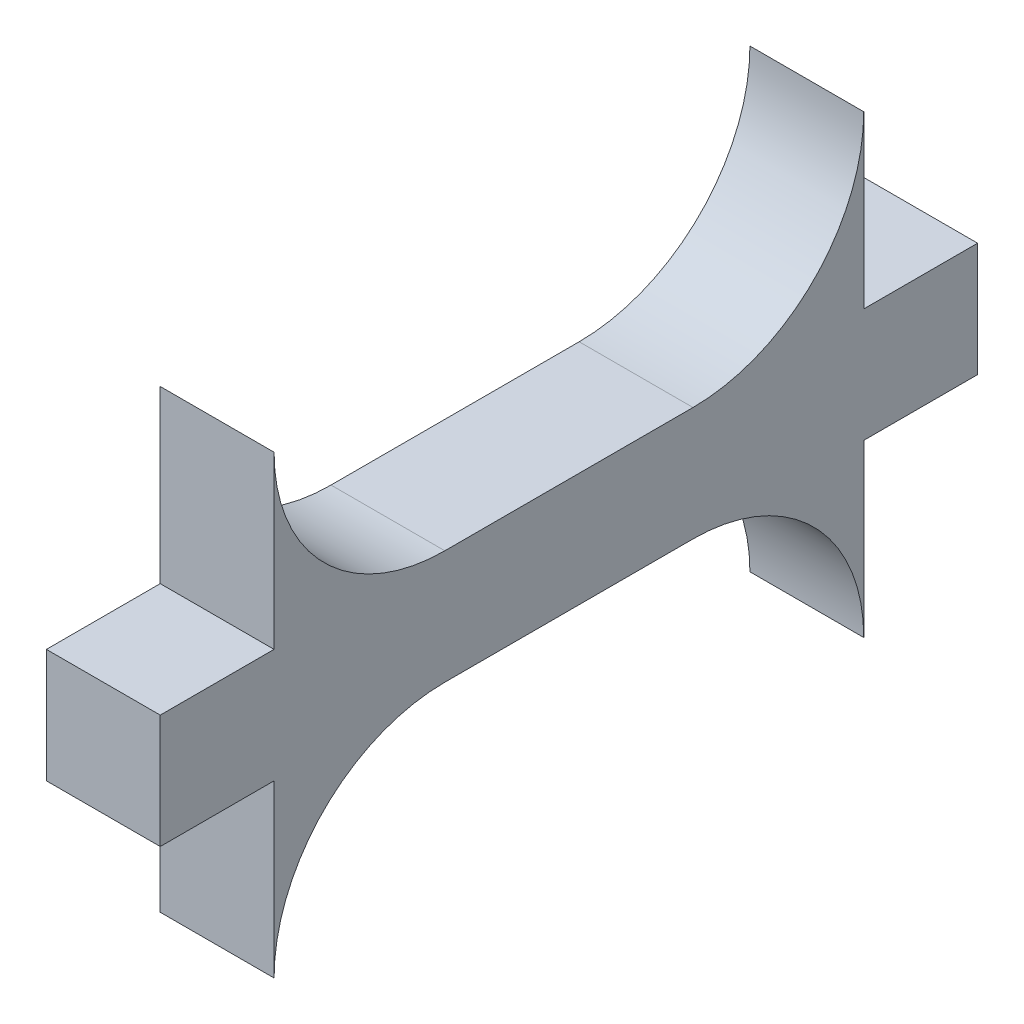
SolidWorks part; units mm, degrees
ref_plane "Front Plane" through (0, 0, 0) normal (0, 0, 1) x (1, 0, 0)
ref_plane "Top Plane" through (0, 0, 0) normal (0, 1, 0) x (1, 0, 0)
ref_plane "Right Plane" through (0, 0, 0) normal (1, 0, 0) x (0, 0, -1)
sketch "Sketch1" plane through (0, 0, 0) normal (1, 0, 0) x (0, 0, -1)
  line L0 (-8.804, 5) -> (12.996, 5)
  line L1 (-23.804, 20) -> (-23.804, -20)
  line L2 (27.996, 20) -> (27.996, -20)
  line L3 (-45.0399, 0) -> (43.1248, 0) construction
  line L4 (-8.804, -5) -> (12.996, -5)
  arc A0 (12.996, 5) -> (27.996, 20) centre (12.996, 20) ccw
  arc A1 (-8.804, 5) -> (-23.804, 20) centre (-8.804, 20) cw
  arc A2 (-8.804, -5) -> (-23.804, -20) centre (-8.804, -20) ccw
  arc A3 (12.996, -5) -> (27.996, -20) centre (12.996, -20) cw
  point P6 (-23.804, 0)
  point P15 (27.996, 0)
  dimension "D1" = 51.8
  dimension "D2" = 21.8
  dimension "D3" = 5
extrude "Boss-Extrude1" add sketch "Sketch1" along normal blind 10
sketch "Sketch2" plane through (0, 0, 23.804) normal (0, 0, 1) x (1, 0, 0)
  line L0 (22.1242, 0) -> (-11.0152, 0) construction
  line L1 (5, 21.8041) -> (5, -22.088) construction
  line L2 (0, 5) -> (10, 5)
  line L3 (10, 5) -> (10, -5)
  line L4 (10, -5) -> (0, -5)
  line L5 (0, -5) -> (0, 5)
  line L6 (10, 20) -> (10, -20) construction
  point P11 (5, 5)
  point P12 (10, 0)
  dimension "D1" = 5
  dimension "D2" = 10
  dimension "D3" = 10
extrude "Boss-Extrude2" add sketch "Sketch2" along normal blind 10
ref_plane "Plane1" through (0, 0, -2.096) normal (0, 0, -1) x (-1, 0, 0)
mirror "Mirror1" about plane through (0, 0, -2.096) normal (0, 0, -1) of "Boss-Extrude2"
